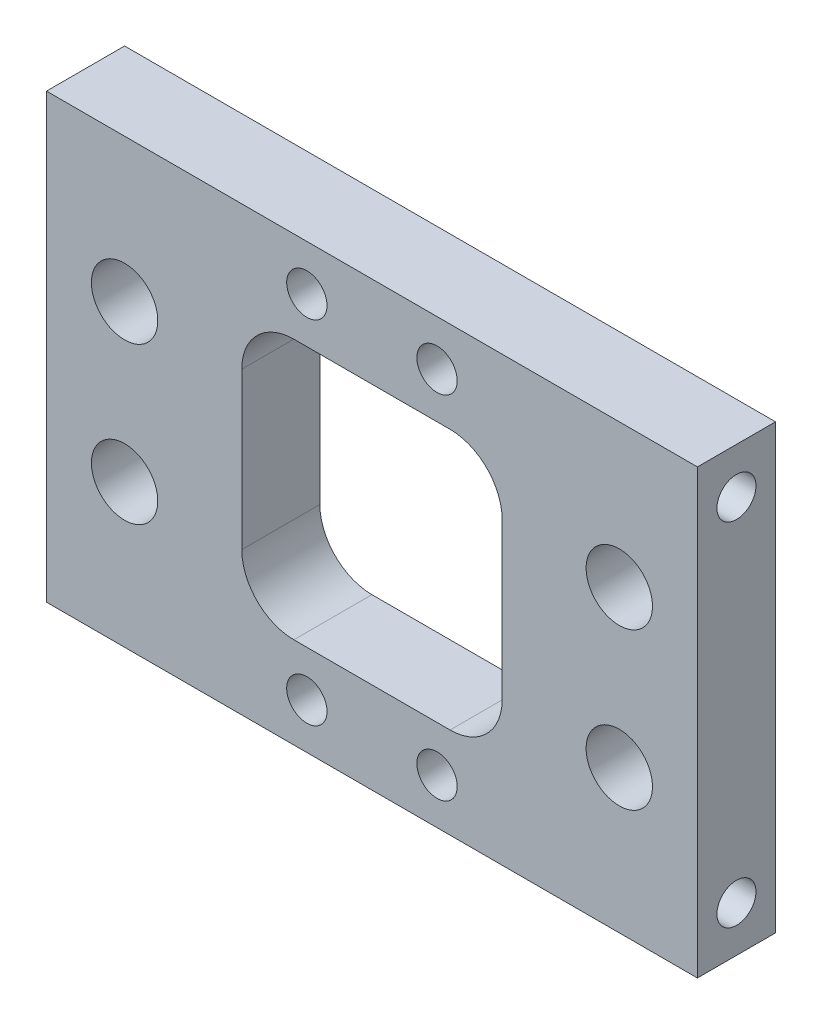
SolidWorks part; units mm, degrees
ref_plane "前视基准面" through (0, 0, 0) normal (0, 0, 1) x (1, 0, 0)
ref_plane "上视基准面" through (0, 0, 0) normal (0, 1, 0) x (1, 0, 0)
ref_plane "右视基准面" through (0, 0, 0) normal (1, 0, 0) x (0, 0, -1)
ref_plane "基准面1" through (0, 0, -3) normal (0, 0, -1) x (-1, 0, 0)
sketch "草图1" plane through (0, 0, -3) normal (0, 0, -1) x (-1, 0, 0)
  line L0 (-25, -17) -> (25, -17)
  line L1 (25, -17) -> (25, 17)
  line L2 (25, 17) -> (-25, 17)
  line L3 (-25, 17) -> (-25, -17)
extrude "凸台-拉伸1" add sketch "草图1" against normal blind 6
sketch "草图2" plane through (0, 0, 3) normal (0, 0, 1) x (1, 0, 0)
  line L0 (10, 10) -> (-10, 10)
  line L1 (-10, 10) -> (-10, -10)
  line L2 (-10, -10) -> (10, -10)
  line L3 (10, -10) -> (10, 10)
extrude "切除-拉伸1" cut sketch "草图2" against normal through all
hole_wizard "Ø5.1 (5.1) 直径孔1" positions "草图4" profile "草图3" hole size "Ø5.1" standard "ANSI Metric" end condition through all
sketch "草图4" plane through (0, 0, -3) normal (0, 0, -1) x (-1, 0, 0)
  point P0 (-19, 6)
  point P1 (19, -6)
  point P2 (-19, -6)
  point P3 (19, 6)
sketch "草图3" plane through (19, 6, -3) normal (1, 0, 0) x (0, 1, 0)
  line L0 (0, 0) -> (0, 6)
  line L1 (0, 6) -> (2.55, 6)
  line L2 (2.55, 6) -> (2.55, 0)
  line L5 (2.55, 0) -> (0, 0)
  line L11 (0, -6.35) -> (0, 107.95) construction
  dimension "通孔孔直径" = 5.1
  dimension "通孔孔深度" = 6
hole_wizard "Ø3.0 (3) 直径孔1" positions "草图6" profile "草图5" hole size "Ø3.0" standard "ANSI Metric"
sketch "草图6" plane through (-25, 0, 0) normal (-1, 0, 0) x (0, 0, 1)
  point P0 (0, -13.5)
  point P1 (0, 13.5)
sketch "草图5" plane through (-25, -13.5, 0) normal (0, 1, 0) x (0, 0, 1)
  line L0 (0, 0) -> (0, 5)
  line L1 (0, 5) -> (1.5, 5)
  line L2 (1.5, 5) -> (1.5, 0)
  line L5 (1.5, 0) -> (0, 0)
  line L10 (0, 5) -> (-1.5, 5) construction
  line L11 (0, -6.35) -> (0, 107.95) construction
  dimension "孔直径" = 3
  dimension "孔深度" = 5
  dimension "导头角度" = 180
hole_wizard "Ø3.0 (3) 直径孔2" positions "草图8" profile "草图7" hole size "Ø3.0" standard "ANSI Metric"
sketch "草图8" plane through (25, 0, 0) normal (1, 0, 0) x (0, 0, -1)
  point P0 (0, -13.5)
  point P1 (0, 13.5)
sketch "草图7" plane through (25, -13.5, 0) normal (0, 1, 0) x (0, 0, -1)
  line L0 (0, 0) -> (0, 5)
  line L1 (0, 5) -> (1.5, 5)
  line L2 (1.5, 5) -> (1.5, 0)
  line L5 (1.5, 0) -> (0, 0)
  line L10 (0, 5) -> (-1.5, 5) construction
  line L11 (0, -6.35) -> (0, 107.95) construction
  dimension "孔直径" = 3
  dimension "孔深度" = 5
  dimension "导头角度" = 180
fillet "圆角1" radius 4 4 edges at (10, -10, 0) (10, 10, 0) (-10, -10, 0) (-10, 10, 0)
sketch "草图9" plane through (0, 0, 3) normal (0, 0, 1) x (1, 0, 0)
  line L0 (25, -17) -> (-25, -17) construction
  line L1 (25, 17) -> (25, -17) construction
  line L2 (-25, -17) -> (-25, 17) construction
  circle A0 centre (5, -13.5) radius 1.55
  circle A2 centre (-5, -13.5) radius 1.55
  dimension "D1" = 3.1
  dimension "D2" = 3.1
  dimension "D3" = 3.5
  dimension "D5" = 3.5
  dimension "D6" = 20
  dimension "D7" = 20
extrude "切除-拉伸3" cut sketch "草图9" against normal up to next
ref_plane "基准面2" through (0, 0, 0) normal (0, -1, 0) x (-1, 0, 0)
mirror "镜向1" about plane through (0, 0, 0) normal (0, -1, 0) of "切除-拉伸3"
